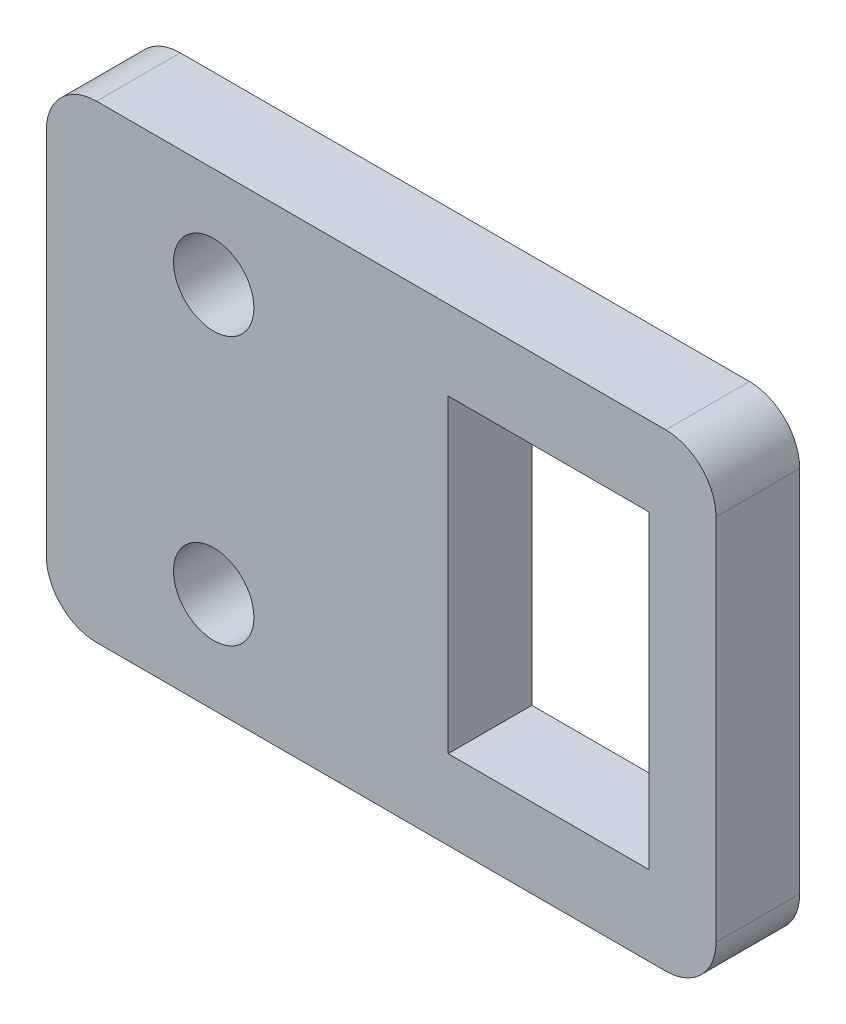
SolidWorks part; units mm, degrees
ref_plane "Front Plane" through (0, 0, 0) normal (0, 0, 1) x (1, 0, 0)
ref_plane "Top Plane" through (0, 0, 0) normal (0, 1, 0) x (1, 0, 0)
ref_plane "Right Plane" through (0, 0, 0) normal (1, 0, 0) x (0, 0, -1)
sketch "Sketch1" plane through (0, 0, 0) normal (0, 0, 1) x (1, 0, 0)
  line L0 (0, 18.4463) -> (0, -22.6049) construction
  line L1 (-20, -14) -> (20, -14)
  line L2 (-20, -14) -> (-20, 14)
  line L3 (-20, 14) -> (20, 14)
  line L4 (20, -14) -> (20, 14)
  line L5 (-20, -14) -> (20, 14) construction
  line L6 (-20, 14) -> (20, -14) construction
  line L7 (-10, 18.4463) -> (-10, -22.6049) construction
  line L8 (-30.2453, 0) -> (32.0077, 0) construction
  line L9 (4, -9.25) -> (16, -9.25)
  line L10 (4, -9.25) -> (4, 9.25)
  line L11 (4, 9.25) -> (16, 9.25)
  line L12 (16, -9.25) -> (16, 9.25)
  line L13 (4, -9.25) -> (16, 9.25) construction
  line L14 (4, 9.25) -> (16, -9.25) construction
  line L15 (10, 18.4463) -> (10, -21.5265) construction
  circle A0 centre (-10, 8) radius 2.4
  circle A1 centre (-10, -8) radius 2.4
  point P0 (0, 0)
  point P10 (10, 0)
  dimension "D8" = 4.8
  dimension "D9" = 6
  dimension "D10" = 6
  dimension "D1" = 40
  dimension "D2" = 28
  dimension "D3" = 20
  dimension "D4" = 10
  dimension "D5" = 18.5
  dimension "D6" = 12
  dimension "D7" = 10
extrude "Boss-Extrude1" add sketch "Sketch1" along normal blind 5
fillet "Fillet1" radius 3 4 edges at (-20, -14, 2.5) (-20, 14, 2.5) (20, -14, 2.5) (20, 14, 2.5)
